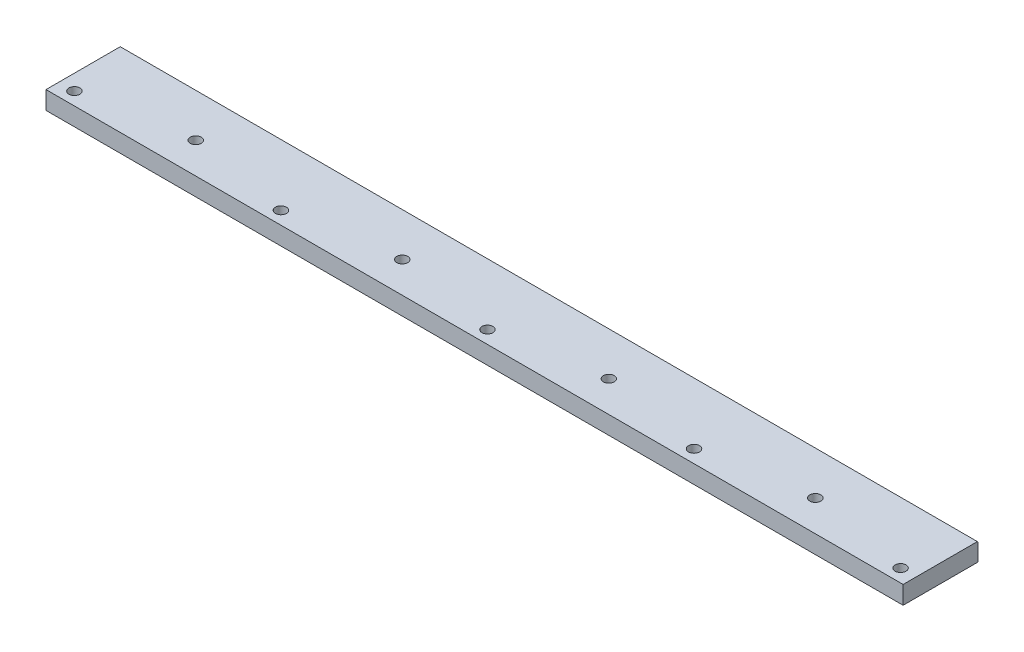
SolidWorks part; units mm, degrees
ref_plane "Front Plane" through (0, 0, 0) normal (0, 0, 1) x (1, 0, 0)
ref_plane "Top Plane" through (0, 0, 0) normal (0, 1, 0) x (1, 0, 0)
ref_plane "Right Plane" through (0, 0, 0) normal (1, 0, 0) x (0, 0, -1)
sketch "Sketch1" plane through (0, 0, 0) normal (0, 1, 0) x (1, 0, 0)
  line L1 (-1054.1, -92.075) -> (1054.1, -92.075)
  line L2 (-1054.1, -92.075) -> (-1054.1, 92.075)
  line L3 (-1054.1, 92.075) -> (1054.1, 92.075)
  line L4 (1054.1, -92.075) -> (1054.1, 92.075)
  line L5 (-1054.1, -92.075) -> (1054.1, 92.075) construction
  line L6 (-1054.1, 92.075) -> (1054.1, -92.075) construction
  point P0 (0, 0)
  dimension "D1" = 1054.1
  dimension "D2" = 92.075
extrude "Boss-Extrude1" add sketch "Sketch1" along normal mid plane 44.45
sketch "Sketch2" plane through (0, 0, 0) normal (0, 1, 0) x (1, 0, 0)
  circle A0 centre (-1016, -60.325) radius 13.4874
  circle A1 centre (-508, -60.325) radius 13.4874
  circle A2 centre (0, -60.325) radius 13.4874
  circle A3 centre (508, -60.325) radius 13.4874
  circle A4 centre (1016, -60.325) radius 13.4874
  point P10 (0, 0)
  dimension "D1" = 26.9748
  dimension "D2" = 26.9748
  dimension "D3" = 26.9748
  dimension "D4" = 26.9748
  dimension "D5" = 26.9748
  dimension "D6" = 508
  dimension "D7" = 1016
  dimension "D8" = 1524
  dimension "D9" = 2032
  dimension "D10" = 60.325
extrude "Cut-Extrude2" cut sketch "Sketch2" along normal blind 88.9 from offset 22.225
sketch "Sketch3" plane through (0, 0, 0) normal (0, 1, 0) x (1, 0, 0)
  circle A0 centre (-1016, -60.325) radius 19.8374
  circle A1 centre (-508, -60.325) radius 19.8374
  circle A2 centre (0, -60.325) radius 19.8374
  circle A3 centre (508, -60.325) radius 19.8374
  circle A4 centre (1016, -60.325) radius 19.8374
  point P10 (0, 0)
  dimension "D1" = 39.6748
  dimension "D2" = 39.6748
  dimension "D3" = 39.6748
  dimension "D4" = 39.6748
  dimension "D5" = 39.6748
  dimension "D6" = 508
  dimension "D7" = 1016
  dimension "D8" = 1524
  dimension "D9" = 2032
  dimension "D10" = 60.325
extrude "Cut-Extrude4" cut sketch "Sketch3" along normal blind 25.4 from offset 22.225
sketch "Sketch4" plane through (0, 0, 0) normal (0, 1, 0) x (1, 0, 0)
  circle A0 centre (-762, -15.875) radius 13.4874
  circle A1 centre (-254, -15.875) radius 13.4874
  circle A2 centre (254, -15.875) radius 13.4874
  circle A3 centre (762, -15.875) radius 13.4874
  point P8 (0, 0)
  dimension "D1" = 26.9748
  dimension "D2" = 26.9748
  dimension "D3" = 26.9748
  dimension "D4" = 26.9748
  dimension "D5" = 508
  dimension "D6" = 1016
  dimension "D7" = 1524
  dimension "D8" = 762
  dimension "D9" = 15.875
extrude "Cut-Extrude6" cut sketch "Sketch4" along normal blind 88.9 from offset 22.225
sketch "Sketch5" plane through (0, 0, 0) normal (0, 1, 0) x (1, 0, 0)
  circle A0 centre (-762, -15.875) radius 19.8374
  circle A1 centre (-254, -15.875) radius 19.8374
  circle A2 centre (254, -15.875) radius 19.8374
  circle A3 centre (762, -15.875) radius 19.8374
  point P8 (0, 0)
  dimension "D1" = 39.6748
  dimension "D2" = 39.6748
  dimension "D3" = 39.6748
  dimension "D4" = 39.6748
  dimension "D5" = 508
  dimension "D6" = 1016
  dimension "D7" = 1524
  dimension "D8" = 762
  dimension "D9" = 15.875
extrude "Cut-Extrude8" cut sketch "Sketch5" along normal blind 25.4 from offset 22.225
chamfer "Chamfer1" distance 1.524 angle 45 2 edges at (0, 22.225, -92.075) (0, -22.225, -92.075)
